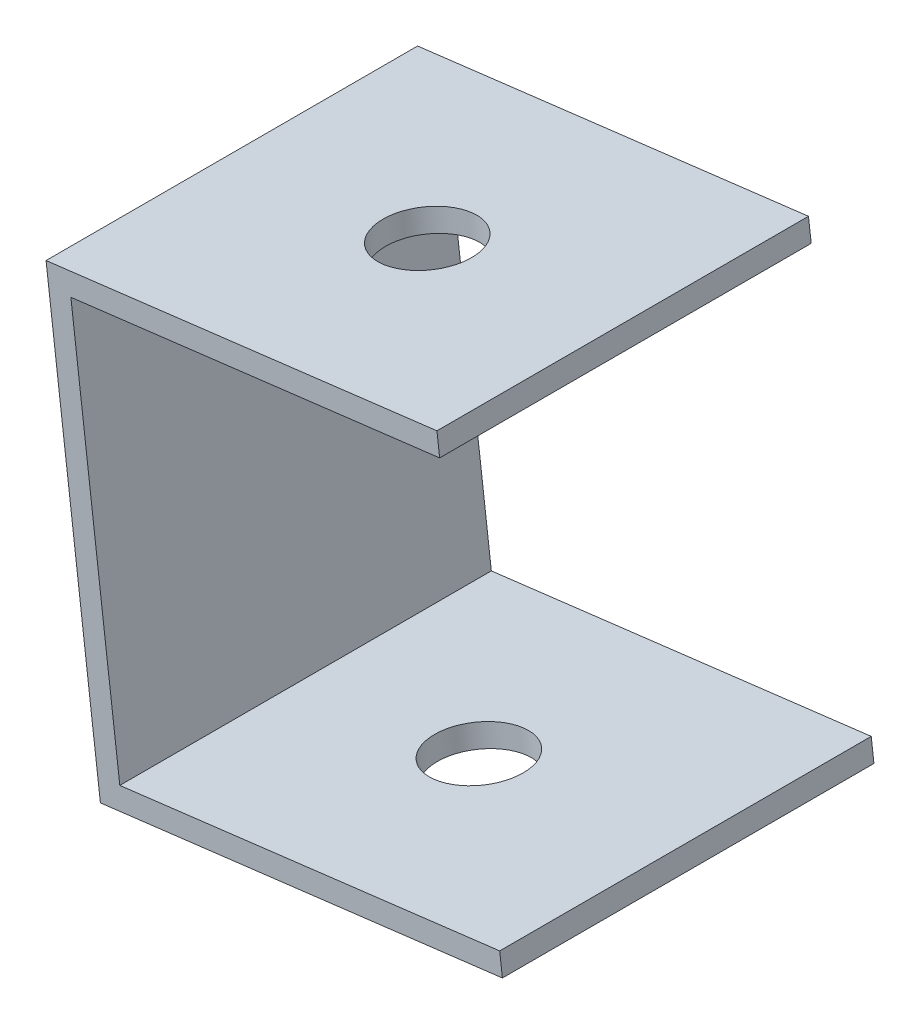
SolidWorks part; units mm, degrees
ref_plane "Front Plane" through (0, 0, 0) normal (0, 0, 1) x (1, 0, 0)
ref_plane "Top Plane" through (0, 0, 0) normal (0, 1, 0) x (1, 0, 0)
ref_plane "Right Plane" through (0, 0, 0) normal (1, 0, 0) x (0, 0, -1)
sketch "Sketch1" plane through (0, 0, 0) normal (0, 0, 1) x (1, 0, 0)
  line L0 (0, 0) -> (-7.3122, 59.5528)
  line L1 (-7.3122, 59.5528) -> (45.2928, 66.0118)
  line L2 (45.2928, 66.0118) -> (45.6584, 63.0342)
  line L3 (45.6584, 63.0342) -> (-3.9689, 56.9407)
  line L4 (-3.9689, 56.9407) -> (2.612, 3.3432)
  line L5 (2.612, 3.3432) -> (53.7366, 9.6206)
  line L6 (53.7366, 9.6206) -> (54.1022, 6.6429)
  line L7 (54.1022, 6.6429) -> (0, 0)
  line L8 (0, 0) -> (-16.5092, 0) construction
  dimension "D1" = 3
  dimension "D2" = 3
  dimension "D3" = 54
  dimension "D4" = 50
  dimension "D5" = 83
extrude "Boss-Extrude1" add sketch "Sketch1" along normal blind 50
sketch "Sketch2" plane through (-7.3122, 59.5528, 0) normal (-0.1219, 0.9925, 0) x (0.9925, 0.1219, 0)
  line L1 (53, 0) -> (0, 0) construction
  line L2 (53, -50) -> (53, 0) construction
  circle A0 centre (26.5, -25) radius 6
  point P5 (26.5, 0)
  point P8 (53, -25)
  dimension "D1" = 12
extrude "Cut-Extrude1" cut sketch "Sketch2" against normal up to surface (60 mm away) up to face at (27.0511, 3.3215, 25)
ref_plane "Plane1" through (-0.0028, 0.0226, 0.2605) normal (0.0106, -0.0865, -0.9962) x (-0.9925, -0.1219, 0)
sketch "Sketch3" plane through (0, 0, 0) normal (-0.9925, -0.1219, 0) x (0, 0, 1)
  line L0 (50, 60) -> (0, 60) construction
  line L1 (0, 60) -> (0, 0) construction
  point P0 (25, 30)
  point P3 (25, 60)
  point P6 (0, 30)
